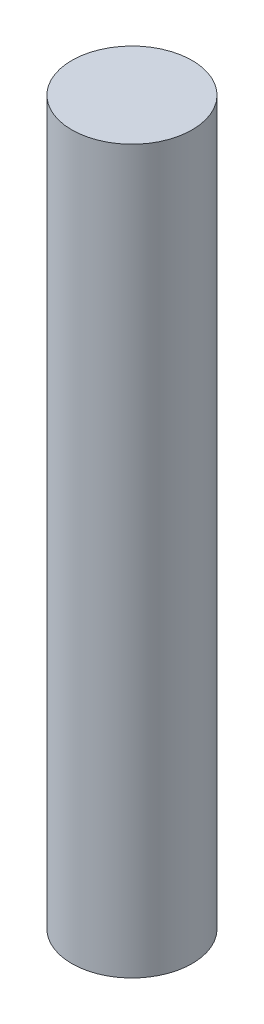
SolidWorks part; units mm, degrees
material "AISI 1020"
ref_plane "Front Plane" through (0, 0, 0) normal (0, 0, 1) x (1, 0, 0)
ref_plane "Top Plane" through (0, 0, 0) normal (0, 1, 0) x (1, 0, 0)
ref_plane "Right Plane" through (0, 0, 0) normal (1, 0, 0) x (0, 0, -1)
sketch "Sketch1" plane through (0, 0, 0) normal (0, 1, 0) x (1, 0, 0)
  circle A0 centre (0, 0) radius 1
  dimension "D1" = 2
extrude "Boss-Extrude1" add sketch "Sketch1" along normal blind 12
equation "\"D1@Sketch1\"=\"impeller dowel diameter\""
equation "\"D1@Boss-Extrude1\"=\"impeller dowel length\" "
equation "\"bearing OD\" = 30mm"
equation "\"bearing outer race thickness\"= 1mm"
equation "\"bearing ID\"= 10mm"
equation "\"bearing depth\"= 9mm"
equation "\"bearing inner race thickness\"= 1mm"
equation "\"small seal OD\" = 20mm"
equation "\"small seal ID\"= 8mm"
equation "\"small seal depth\" = 8.3mm"
equation "\"big seal OD\" = 27mm"
equation "\"big seal ID\"= 15mm"
equation "\"big seal depth\"= 8.3mm"
equation "\"z\" = 8 \t\t\t\t'number of blades"
equation "\"de\" = 0.426in \t\t\t\t'entrance eye diameter"
equation "\"d2\" = 2.097in \t\t\t\t'outer diameter of the impeller "
equation "\"d_exit\" = 0.18in \t\t\t'volute throat aka D4"
equation "\"theta\" = 15"
equation "\"b2\" = .071in\t\t\t\t\t\t\t\t'tip height from disc surface at d2"
equation "\"b1\" = \"b2\" + (\"d2\"/2 - \"de\"/2)*sin(\"theta\")\t\t\t\t'tip height from disc surface at inlet eye"
equation "\"s\" = ( 1/\"z\")*(3.14*\"de\" - (3.14*(\"de\"^2) / (4*(\"b1\"))))\t\t'thickness of blades, calculated from area"
equation "\"s_opening\" = (3.14*\"de\" - \"z\"*\"s\")/\"z\"\t\t\t\t\t'ideal gap between blades, calculated from area"
equation "\"area_eye\"=3.14*(\"de\"^2)/4\t\t\t\t\t\t'eye area"
equation "\"single_channel_area\"=\"s_opening\"*\"b1\"\t\t\t\t\t'ideal area between two blades"
equation "\"impeller upper clearance\"= .5mm"
equation "\"impeller horizontal clearance\"= (\"d2\"*1.15 - \"d2\")/2 \t\t\t\t\t'clearance based on D2-D3 ratio for circular volute, ranges 1.15 to 1.2"
equation "\"impeller bottom clearance\"= .5mm"
equation "\"impeller base thickness\"= 2mm"
equation "\"impeller boss depth\" = \"shaft impeller section length\" + 3mm + \"impeller bolt head depth\" - \"impeller base thickness\""
equation "\"impeller dowel diameter\" = 2mm"
equation "\"impeller bolt head diameter\" = 7.5mm"
equation "\"impeller bolt head depth\" = 4mm"
equation "\"impeller boss diameter\" = \"big seal ID\""
equation "\"impeller shaft bore\"= 8mm"
equation "\"impeller shaft bore depth\" = \"impeller boss depth\" + \"impeller base thickness\" - \"impeller bolt head depth\" - 3mm"
equation "\"impeller dowel length\" = 2mm*2 + \"impeller shaft bore\""
equation "\"impeller screw hole bore\" = 4mm"
equation "\"shaft impeller screw hole diameter\" = \"impeller screw hole bore\""
equation "\"shaft impeller section length\" = \"big seal plate thickness\"/2 + \"impeller bottom clearance\" + \"impeller base thickness\" - \"impeller bolt head depth\" - 3mm"
equation "\"shaft impeller screw hole depth\" = \"shaft impeller section length\"-\"impeller dowel diameter\"-2mm"
equation "\"shaft impeller section diameter\" = \"impeller shaft bore\""
equation "\"shaft seal section diameter\"=\"small seal ID\""
equation "\"shaft seal section length\"= \"big seal plate thickness\"/2 + \"small seal bore\" + 2mm"
equation "\"shaft bearing section diameter\" = \"bearing ID\""
equation "\"shaft bearing section length\" = \"bearing bore\""
equation "\"shaft bearing stop diameter\" = \"bearing ID\" + 2mm"
equation "\"shaft bearing stop length\" = 2mm"
equation "\"shaft coupler section diameter\" = 8mm"
equation "\"shaft coupler section length\" = \"shaft bearing stop length\" + \"coupler length\"/2 + 4mm"
equation "\"coupler set screw drill hole ID\"= 6mm"
equation "\"coupler set screw 1 distance\"= \"motor mount shaft hole depth\" / 3"
equation "\"coupler set screw 2 distance\"= \"motor mount shaft hole depth\" * 4 / 5"
equation "\"coupler motor shaft hole ID\"= 8mm"
equation "\"coupler impeller shaft hole ID\"= \"shaft coupler section diameter\""
equation "\"coupler OD\"= 17mm"
equation "\"coupler length\"= 25mm"
equation "\"bearing plate bearing recess\"= \"bearing depth\""
equation "\"bearing plate bearing clearance\"= \"shaft bearing stop length\" + 2mm"
equation "\"seal plate small seal recess depth\"= \"small seal depth\""
equation "\"seal plate small seal recess OD\"= \"small seal OD\""
equation "\"seal plate lip depth\"= 2mm"
equation "\"seal plate lip ID\"= \"small seal OD\" - 3mm"
equation "\"seal plate thickness\"= \"seal plate small seal recess depth\" + \"seal plate lip depth\" + \"seal plate lip depth\""
equation "\"motor to housing distance\" = \"motor shaft pride\" + \"shaft coupler section length\" - \"bearing plate bearing stop depth\" + 2mm"
equation "\"motor mount pattern diameter\"= 30mm"
equation "\"motor mount to housing m8 screw hole diameter\"= 8.5mm"
equation "\"motor mount to housing m8 screw post radius\"= ( 3 * \"motor mount to housing m8 screw hole diameter\" ) / 2"
equation "\"motor mount to housing m8 pattern diameter\"= 100mm"
equation "\"motor mount to housing m4 screw hole diameter\"= 4mm"
equation "\"motor mount to housing m4 head diameter\"= 7.25mm"
equation "\"motor mount to housing m4 head depth\"= 4mm"
equation "\"motor mount plate thickness\"= 8mm + \"motor mount m4 head depth\""
equation "\"housing bearing seat lip thickness\"= 2mm"
equation "\"housing base thickness\"= \"housing bearing seat lip thickness\" + \"bearing depth\""
equation "\"impeller cavity center height\"= \"impeller bottom clearance\" + \"impeller upper clearance\" + \"final impeller center height\""
equation "\"impeller cavity diameter\"= 2 * \"impeller horizontal clearance\" + \"d2\" \t\t\t'called D3 analytically"
equation "\"impeller cavity outer height\"= \"impeller bottom clearance\" + \"impeller upper clearance\" + \"impeller base thickness\" + \"b2\" \t\t\t'this is height at impeller diameter d2, not at d3"
equation "\"housing top o-ring channel height\"= 1.5mm"
equation "\"housing top o ring channel width\"= 1.5mm"
equation "\"housing top o-ring diameter\"= 3in"
equation "\"housing top threaded inlet depth\"= 8mm"
equation "\"housing top total thickness\"= \"housing top threaded inlet depth\" + \"impeller cavity center height\""
equation "\"housing top total width\"= 10mm"
equation "\"housing top exit threaded diameter\"= 8mm"
equation "\"housing top exit threaded depth\"= 8mm"
equation "\"motor shaft pride\"= 32mm"
equation "\"motor shaft flat section length from tip\"= 25.7mm"
equation "\"motor shaft bore end clearance\"= 2mm"
equation "\"coupler shaft to motor clearance\" = 2mm"
equation "\"motor mount shaft hole depth\"= \"motor shaft pride\""
